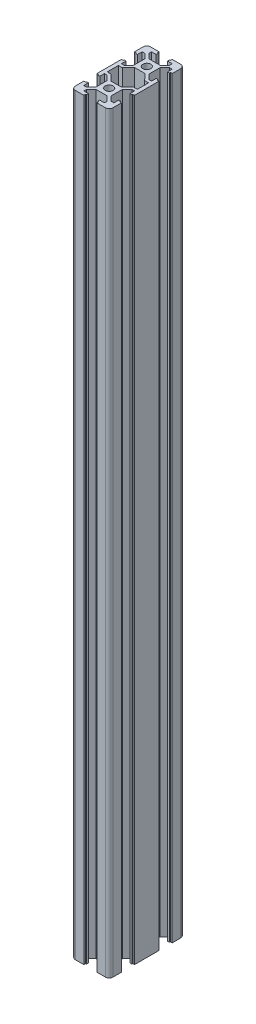
SolidWorks part; units mm, degrees
ref_plane "Спереди" through (0, 0, 0) normal (0, 0, 1) x (1, 0, 0)
ref_plane "Сверху" through (0, 0, 0) normal (0, 1, 0) x (1, 0, 0)
ref_plane "Справа" through (0, 0, 0) normal (1, 0, 0) x (0, 0, -1)
other "Configuration Table"
sketch "Эскиз2" plane through (0, 0, 0) normal (0, 1, 0) x (1, 0, 0)
  line L0 (0, 0) -> (0, 14.0607) construction
  line L1 (-10, -20) -> (-3.5, -20)
  line L2 (-10, -20) -> (-10, -13.5)
  line L3 (-10, 20) -> (-3.5, 20)
  line L4 (10, -20) -> (10, -13.5)
  line L5 (-10, -20) -> (10, 20) construction
  line L6 (-10, 20) -> (10, -20) construction
  line L7 (0, 0) -> (-10, 0) construction
  line L9 (-3, 18.005) -> (-5.5, 18.005)
  line L10 (-5.5, 18.005) -> (-5.5, 16.5607)
  line L11 (-5.5, 16.5607) -> (-3, 14.0607)
  line L12 (-3, 14.0607) -> (3, 14.0607)
  line L13 (-10, 20) -> (8.005, 1.995) construction
  line L14 (-5, 10) -> (5, 10) construction
  line L15 (-4.0607, 13) -> (-4.0607, 7)
  line L28 (4.0607, 13) -> (4.0607, 7)
  line L36 (-10, 13.5) -> (-10, 20)
  line L38 (-3, -14.0607) -> (3, -14.0607)
  line L45 (10, 13.5) -> (10, 20)
  line L60 (-4.0607, -13) -> (-4.0607, -7)
  line L61 (4.0607, -13) -> (4.0607, -7)
  line L66 (-2.7646, 6.2607) -> (2.7646, 6.2607)
  line L67 (2.7646, 6.2607) -> (5.9203, 2.9353)
  line L68 (5.9203, 2.9353) -> (8.005, 2.9353)
  line L69 (8.005, 2.9353) -> (8.005, -3.019)
  line L70 (8.005, -3.019) -> (5.9203, -3.019)
  line L71 (5.9203, -3.019) -> (2.6787, -6.2607)
  line L72 (2.6787, -6.2607) -> (-2.6787, -6.2607)
  line L73 (-2.6787, -6.2607) -> (-5.9203, -3.019)
  line L74 (-5.9203, -3.019) -> (-8.005, -3.019)
  line L75 (-8.005, -3.019) -> (-8.005, 2.9353)
  line L76 (-8.005, 2.9353) -> (-5.9203, 2.9353)
  line L77 (-5.9203, 2.9353) -> (-2.7646, 6.2607)
  line L78 (10, -6.5) -> (10, 6.5)
  line L79 (-10, -6.5) -> (-10, 6.5)
  line L80 (3.5, -20) -> (10, -20)
  line L81 (3.5, 20) -> (10, 20)
  line L82 (-3, 18.005) -> (-3, 19.005)
  line L83 (-3, 19.005) -> (-3.5, 19)
  line L84 (-3.5, 19) -> (-3.5, 20)
  line L85 (0, 14.0607) -> (0, 18.005) construction
  line L86 (0, 18.005) -> (-3, 18.005) construction
  line L87 (5.5, 16.5607) -> (3, 14.0607)
  line L88 (5.5, 18.005) -> (5.5, 16.5607)
  line L89 (3, 18.005) -> (5.5, 18.005)
  line L90 (3, 18.005) -> (3, 19.005)
  line L91 (3, 19.005) -> (3.5, 19)
  line L92 (3.5, 19) -> (3.5, 20)
  line L93 (-9, 13.5) -> (-10, 13.5)
  line L94 (-9.005, 13) -> (-9, 13.5)
  line L95 (-8.005, 13) -> (-9.005, 13)
  line L96 (-8.005, 13) -> (-8.005, 15.5)
  line L97 (-8.005, 15.5) -> (-6.5607, 15.5)
  line L98 (-6.5607, 15.5) -> (-4.0607, 13)
  line L99 (-9, 6.5) -> (-10, 6.5)
  line L100 (-9.005, 7) -> (-9, 6.5)
  line L101 (-8.005, 7) -> (-9.005, 7)
  line L102 (-8.005, 7) -> (-8.005, 4.5)
  line L103 (-8.005, 4.5) -> (-6.5607, 4.5)
  line L104 (-6.5607, 4.5) -> (-4.0607, 7)
  line L105 (-3.5, -19) -> (-3.5, -20)
  line L106 (-3, -19.005) -> (-3.5, -19)
  line L107 (-3, -18.005) -> (-3, -19.005)
  line L108 (-3, -18.005) -> (-5.5, -18.005)
  line L109 (-5.5, -18.005) -> (-5.5, -16.5607)
  line L110 (-5.5, -16.5607) -> (-3, -14.0607)
  line L111 (5.5, -16.5607) -> (3, -14.0607)
  line L112 (5.5, -18.005) -> (5.5, -16.5607)
  line L113 (3, -18.005) -> (5.5, -18.005)
  line L114 (3, -18.005) -> (3, -19.005)
  line L115 (3, -19.005) -> (3.5, -19)
  line L116 (3.5, -19) -> (3.5, -20)
  line L117 (-9, -13.5) -> (-10, -13.5)
  line L118 (-9.005, -13) -> (-9, -13.5)
  line L119 (-8.005, -13) -> (-9.005, -13)
  line L120 (-8.005, -13) -> (-8.005, -15.5)
  line L121 (-8.005, -15.5) -> (-6.5607, -15.5)
  line L122 (-6.5607, -15.5) -> (-4.0607, -13)
  line L124 (-9, -6.5) -> (-10, -6.5)
  line L125 (-9.005, -7) -> (-9, -6.5)
  line L126 (-8.005, -7) -> (-9.005, -7)
  line L127 (-8.005, -7) -> (-8.005, -4.5)
  line L128 (-8.005, -4.5) -> (-6.5607, -4.5)
  line L129 (-6.5607, -4.5) -> (-4.0607, -7)
  line L130 (9, 6.5) -> (10, 6.5)
  line L131 (9.005, 7) -> (9, 6.5)
  line L132 (8.005, 7) -> (9.005, 7)
  line L133 (8.005, 7) -> (8.005, 4.5)
  line L134 (8.005, 4.5) -> (6.5607, 4.5)
  line L135 (6.5607, 4.5) -> (4.0607, 7)
  line L137 (9, 13.5) -> (10, 13.5)
  line L138 (9.005, 13) -> (9, 13.5)
  line L139 (8.005, 13) -> (9.005, 13)
  line L140 (8.005, 13) -> (8.005, 15.5)
  line L141 (8.005, 15.5) -> (6.5607, 15.5)
  line L142 (6.5607, 15.5) -> (4.0607, 13)
  line L143 (9.005, -13) -> (9, -13.5)
  line L144 (9.005, -7) -> (9, -6.5)
  line L146 (6.5607, -15.5) -> (4.0607, -13)
  line L147 (8.005, -15.5) -> (6.5607, -15.5)
  line L148 (8.005, -13) -> (8.005, -15.5)
  line L149 (8.005, -13) -> (9.005, -13)
  line L150 (9, -13.5) -> (10, -13.5)
  line L151 (9, -6.5) -> (10, -6.5)
  line L152 (8.005, -7) -> (9.005, -7)
  line L153 (8.005, -7) -> (8.005, -4.5)
  line L154 (8.005, -4.5) -> (6.5607, -4.5)
  line L155 (6.5607, -4.5) -> (4.0607, -7)
  circle A0 centre (0, 10) radius 2.1
  circle A1 centre (0, -10) radius 2.1
  point P0 (0, 0)
  point P35 (0, 14.0607)
  point P66 (4.0607, 10)
  point P71 (-4.0607, 10)
  point P117 (0, 0)
  point P118 (0, 0)
  point P119 (0, 0)
  point P120 (0, 0)
  dimension "D17" = 4.2
  dimension "D1" = 20
  dimension "D2" = 40
  dimension "D3" = 5.5
  dimension "D4" = 1
  dimension "D5" = 6
  dimension "D6" = 3
  dimension "D7" = 90
  dimension "D8" = 0.75
  dimension "D9" = 10
  dimension "D10" = 7.8
  dimension "D11" = 7.8
  dimension "D12" = 3.5
  dimension "D13" = 3
  dimension "D14" = 3.9444
  dimension "D15" = 1.5
  dimension "D16" = 1.5
  dimension "D18" = 1
  dimension "D19" = 1.5
  dimension "D20" = 1.5
  dimension "D21" = 5.9543
  dimension "D22" = 5.9543
extrude "Бобышка-Вытянуть1" add sketch "Эскиз2" along normal blind 400
fillet "Скругление1" radius 2 4 edges at (-10, 200, 20) (10, 200, 20) (10, 200, -20) (-10, 200, -20)
fillet "Скругление2" radius 0.2 12 edges at (-3.5, 200, 19) (3.5, 200, 19) (9, 200, 13.5) (9, 200, 6.5) (9, 200, -6.5) (9, 200, -13.5) (3.5, 200, -19) (-3.5, 200, -19) (-9, 200, -13.5) (-9, 200, 6.5) (-9, 200, 13.5) (-9, 200, -6.5)
